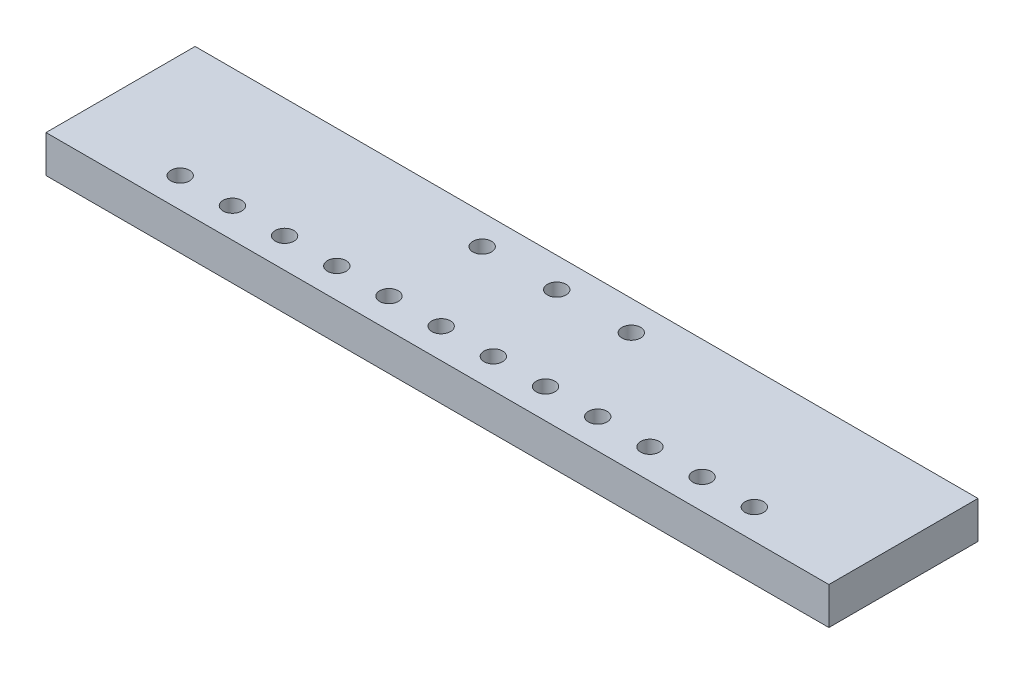
SolidWorks part; units mm, degrees
ref_plane "Front Plane" through (0, 0, 0) normal (0, 0, 1) x (1, 0, 0)
ref_plane "Top Plane" through (0, 0, 0) normal (0, 1, 0) x (1, 0, 0)
ref_plane "Right Plane" through (0, 0, 0) normal (1, 0, 0) x (0, 0, -1)
sketch "Sketch1" plane through (0, 0, 0) normal (0, 1, 0) x (1, 0, 0)
  line L1 (-66.675, -12.7) -> (66.675, -12.7)
  line L2 (-66.675, -12.7) -> (-66.675, 12.7)
  line L3 (-66.675, 12.7) -> (66.675, 12.7)
  line L4 (66.675, -12.7) -> (66.675, 12.7)
  line L5 (-66.675, -12.7) -> (66.675, 12.7) construction
  line L6 (-66.675, 12.7) -> (66.675, -12.7) construction
  point P0 (0, 0)
  dimension "D1" = 133.35
  dimension "D2" = 25.4
extrude "Boss-Extrude1" add sketch "Sketch1" along normal blind 6.35
sketch "Sketch2" plane through (0, 6.35, 0) normal (0, 1, 0) x (1, 0, 0)
  line L0 (-4.445, -7.62) -> (4.445, -7.62) construction
  line L1 (66.675, 12.7) -> (-66.675, 12.7) construction
  line L2 (-66.675, -12.7) -> (66.675, -12.7) construction
  circle A0 centre (0, 7.62) radius 1.5875
  circle A1 centre (-12.7, 7.62) radius 1.5875
  circle A2 centre (12.7, 7.62) radius 1.5875
  circle A3 centre (-48.895, -7.62) radius 1.5875
  circle A4 centre (-40.005, -7.62) radius 1.5875
  circle A5 centre (-31.115, -7.62) radius 1.5875
  circle A6 centre (-13.335, -7.62) radius 1.5875
  circle A7 centre (-22.225, -7.62) radius 1.5875
  circle A8 centre (-4.445, -7.62) radius 1.5875
  circle A9 centre (4.445, -7.62) radius 1.5875
  circle A10 centre (13.335, -7.62) radius 1.5875
  circle A11 centre (22.225, -7.62) radius 1.5875
  circle A12 centre (31.115, -7.62) radius 1.5875
  circle A13 centre (40.005, -7.62) radius 1.5875
  circle A14 centre (48.895, -7.62) radius 1.5875
  point P31 (0, -7.62)
  point P32 (0, 0)
  point P33 (0, 0)
  point P34 (0, 0)
  point P35 (0, 0)
  point P36 (0, 0)
  point P37 (0, 0)
  dimension "D1" = 3.175
  dimension "D2" = 3.175
  dimension "D3" = 3.175
  dimension "D6" = 3.175
  dimension "D7" = 3.175
  dimension "D8" = 3.175
  dimension "D9" = 3.175
  dimension "D10" = 3.175
  dimension "D11" = 3.175
  dimension "D12" = 3.175
  dimension "D13" = 3.175
  dimension "D14" = 3.175
  dimension "D15" = 3.175
  dimension "D16" = 3.175
  dimension "D17" = 3.175
  dimension "D4" = 12.7
  dimension "D5" = 12.7
  dimension "D18" = 8.89
  dimension "D20" = 8.89
  dimension "D19" = 8.89
  dimension "D21" = 8.89
  dimension "D23" = 8.89
  dimension "D24" = 8.89
  dimension "D22" = 8.89
  dimension "D25" = 8.89
  dimension "D26" = 8.89
  dimension "D27" = 8.89
  dimension "D28" = 8.89
  dimension "D29" = 5.08
  dimension "D30" = 5.08
extrude "Cut-Extrude1" cut sketch "Sketch2" against normal up to surface (6.35 mm away) up to face at (0, 0, 0)
equation "\"bus-bar-width\"= 1in"
equation "\"bus-bar-thickness\"= .25in"
equation "\"bus-bar-length\"= 5.25in"
equation "\"D1@Sketch1\"=\"bus-bar-length\""
equation "\"D2@Sketch1\"=\"bus-bar-width\""
equation "\"D1@Boss-Extrude1\"=\"bus-bar-thickness\""
equation "\"bus-bar-hole-diameter\"= .125in"
equation "\"D1@Sketch2\"=\"bus-bar-hole-diameter\""
equation "\"D2@Sketch2\"=\"bus-bar-hole-diameter\""
equation "\"D3@Sketch2\"=\"bus-bar-hole-diameter\""
equation "\"distance-between-hole-centers-converter-side\"= .5in"
equation "\"D4@Sketch2\"=\"distance-between-hole-centers-converter-side\""
equation "\"D5@Sketch2\"=\"distance-between-hole-centers-converter-side\""
equation "\"D6@Sketch2\"=\"bus-bar-hole-diameter\""
equation "\"D7@Sketch2\"=\"bus-bar-hole-diameter\""
equation "\"D8@Sketch2\"=\"bus-bar-hole-diameter\""
equation "\"D9@Sketch2\"=\"bus-bar-hole-diameter\""
equation "\"D10@Sketch2\"=\"bus-bar-hole-diameter\""
equation "\"D11@Sketch2\"=\"bus-bar-hole-diameter\""
equation "\"D12@Sketch2\"=\"bus-bar-hole-diameter\""
equation "\"D13@Sketch2\"=\"bus-bar-hole-diameter\""
equation "\"D14@Sketch2\"=\"bus-bar-hole-diameter\""
equation "\"D15@Sketch2\"=\"bus-bar-hole-diameter\""
equation "\"D16@Sketch2\"=\"bus-bar-hole-diameter\""
equation "\"D17@Sketch2\"=\"bus-bar-hole-diameter\""
equation "\"distance-between-hole-centers-led-strip-side\"= .35in"
equation "\"D18@Sketch2\"=\"distance-between-hole-centers-led-strip-side\""
equation "\"D20@Sketch2\"=\"distance-between-hole-centers-led-strip-side\""
equation "\"D19@Sketch2\"=\"distance-between-hole-centers-led-strip-side\""
equation "\"D21@Sketch2\"=\"distance-between-hole-centers-led-strip-side\""
equation "\"D23@Sketch2\"=\"distance-between-hole-centers-led-strip-side\""
equation "\"D24@Sketch2\"=\"distance-between-hole-centers-led-strip-side\""
equation "\"D22@Sketch2\"=\"distance-between-hole-centers-led-strip-side\""
equation "\"D25@Sketch2\"=\"distance-between-hole-centers-led-strip-side\""
equation "\"D26@Sketch2\"=\"distance-between-hole-centers-led-strip-side\""
equation "\"D27@Sketch2\"=\"distance-between-hole-centers-led-strip-side\""
equation "\"D28@Sketch2\"=\"distance-between-hole-centers-led-strip-side\""
equation "\"hole-center-to-edge\"= .2in"
equation "\"D29@Sketch2\"=\"hole-center-to-edge\""
equation "\"D30@Sketch2\"=\"hole-center-to-edge\""
